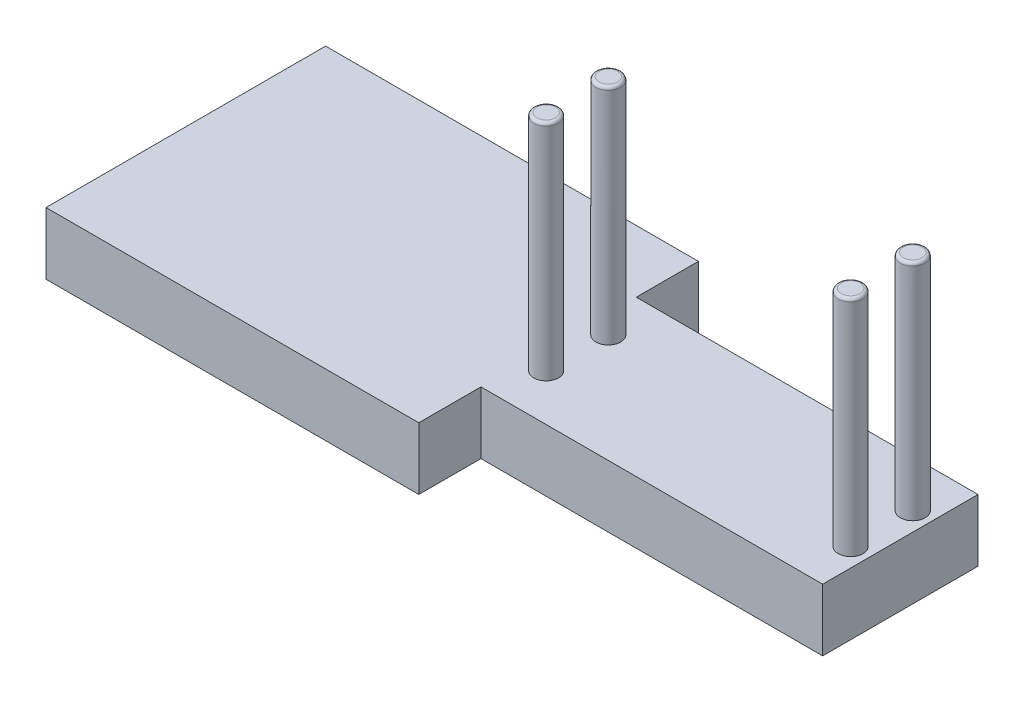
SolidWorks part; units mm, degrees
ref_plane "Front Plane" through (0, 0, 0) normal (0, 0, 1) x (1, 0, 0)
ref_plane "Top Plane" through (0, 0, 0) normal (0, 1, 0) x (1, 0, 0)
ref_plane "Right Plane" through (0, 0, 0) normal (1, 0, 0) x (0, 0, -1)
sketch "Sketch1" plane through (0, 0, 0) normal (0, 1, 0) x (1, 0, 0)
  line L0 (30, -12.5) -> (30, -22.5)
  line L1 (-30, 22.5) -> (30, 22.5)
  line L2 (-30, 22.5) -> (-30, -22.5)
  line L3 (-30, -22.5) -> (30, -22.5)
  line L4 (30, 22.5) -> (30, 12.5)
  line L5 (-30, 22.5) -> (30, -22.5) construction
  line L6 (-30, -22.5) -> (30, 22.5) construction
  line L7 (33, 12.5) -> (33, -12.5) construction
  line L8 (30, 12.5) -> (85, 12.5)
  line L10 (30, -12.5) -> (85, -12.5)
  line L11 (85, 12.5) -> (85, -12.5)
  line L12 (82, 12.5) -> (82, -12.5) construction
  point P0 (0, 0)
  dimension "D1" = 45
  dimension "D2" = 60
  dimension "D3" = 55
  dimension "D4" = 25
  dimension "D5" = 10
  dimension "D6" = 49
  dimension "D7" = 3
extrude "Boss-Extrude2" add sketch "Sketch1" along normal blind 10
sketch "Sketch6" plane through (0, 10, 0) normal (0, 1, 0) x (1, 0, 0)
  line L0 (33, 12.5) -> (33, -12.5) construction
  line L1 (85, 12.5) -> (30, 12.5) construction
  line L2 (30, -12.5) -> (85, -12.5) construction
  line L3 (82, 12.5) -> (82, -12.5) construction
  line L4 (-55, 0) -> (55, 0) construction
  circle A0 centre (33, 5) radius 2
  circle A1 centre (33, -5) radius 2
  circle A2 centre (82, 5) radius 2
  circle A3 centre (82, -5) radius 2
  dimension "D3" = 4
  dimension "D4" = 4
  dimension "D5" = 4
  dimension "D6" = 4
  dimension "D1" = 49
  dimension "D2" = 3
  dimension "D7" = 5
  dimension "D8" = 5
  dimension "D9" = 5
  dimension "D10" = 5
extrude "Boss-Extrude3" add sketch "Sketch6" along normal blind 36 contours A2 | A1 | A0 | A3
fillet "Fillet2" radius 0.5 4 edges at (82, 46, 7) (82, 46, -3) (33, 46, 7) (33, 46, -3)
